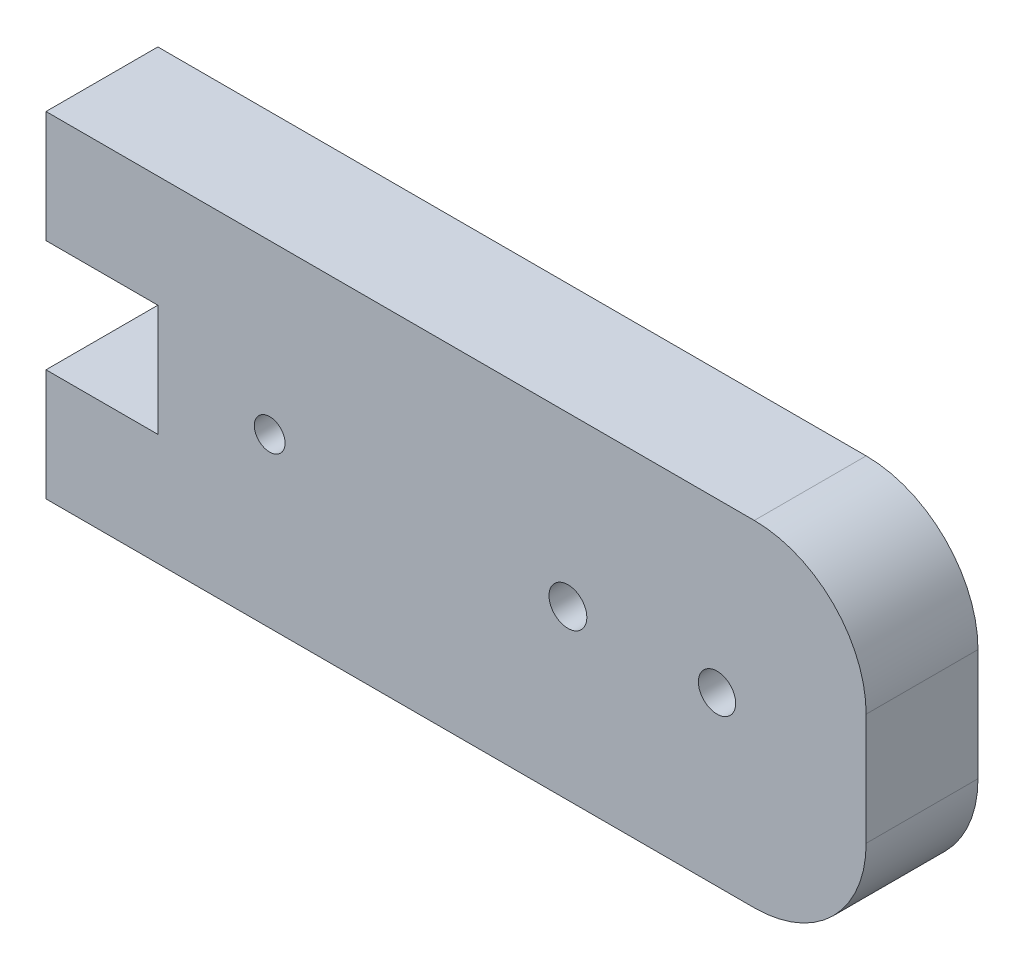
SolidWorks part; units mm, degrees
ref_plane "Front Plane" through (0, 0, 0) normal (0, 0, 1) x (1, 0, 0)
ref_plane "Top Plane" through (0, 0, 0) normal (0, 1, 0) x (1, 0, 0)
ref_plane "Right Plane" through (0, 0, 0) normal (1, 0, 0) x (0, 0, -1)
sketch "Sketch2" plane through (0, 0, 0) normal (0, 0, 1) x (1, 0, 0)
  line L0 (-5, 0) -> (12.2073, 0) construction
  line L1 (-11, 4.5) -> (11, 4.5)
  line L2 (-11, 4.5) -> (-11, 1.5)
  line L3 (-11, -4.5) -> (11, -4.5)
  line L4 (11, 4.5) -> (11, 0.5)
  line L5 (-11, 4.5) -> (11, -4.5) construction
  line L6 (-11, -4.5) -> (11, 4.5) construction
  line L7 (-11, 1.5) -> (-8, 1.5)
  line L8 (-11, -1.5) -> (-11, -4.5)
  line L9 (-11, -1.5) -> (-8, -1.5)
  line L10 (-8, 1.5) -> (-8, -1.5)
  line L11 (-14, 1.5) -> (-8, -1.5) construction
  line L12 (-14, -1.5) -> (-8, 1.5) construction
  line L13 (11, -0.5) -> (11, -4.5)
  line L14 (11, 0.5) -> (11, -0.5)
  circle A0 centre (7, 0) radius 0.5
  circle A1 centre (3, 0) radius 0.5073
  circle A2 centre (-5, 0) radius 0.4122
  point P0 (0, 0)
  point P6 (-11, 0)
  dimension "D7" = 4
  dimension "D8" = 1
  dimension "D1" = 22
  dimension "D2" = 9
  dimension "D3" = 6
  dimension "D4" = 3
  dimension "D5" = 8
  dimension "D6" = 8
extrude "Boss-Extrude1" add sketch "Sketch2" along normal blind 3
fillet "Fillet1" radius 3 2 edges at (11, -4.5, 1.5) (11, 4.5, 1.5)
